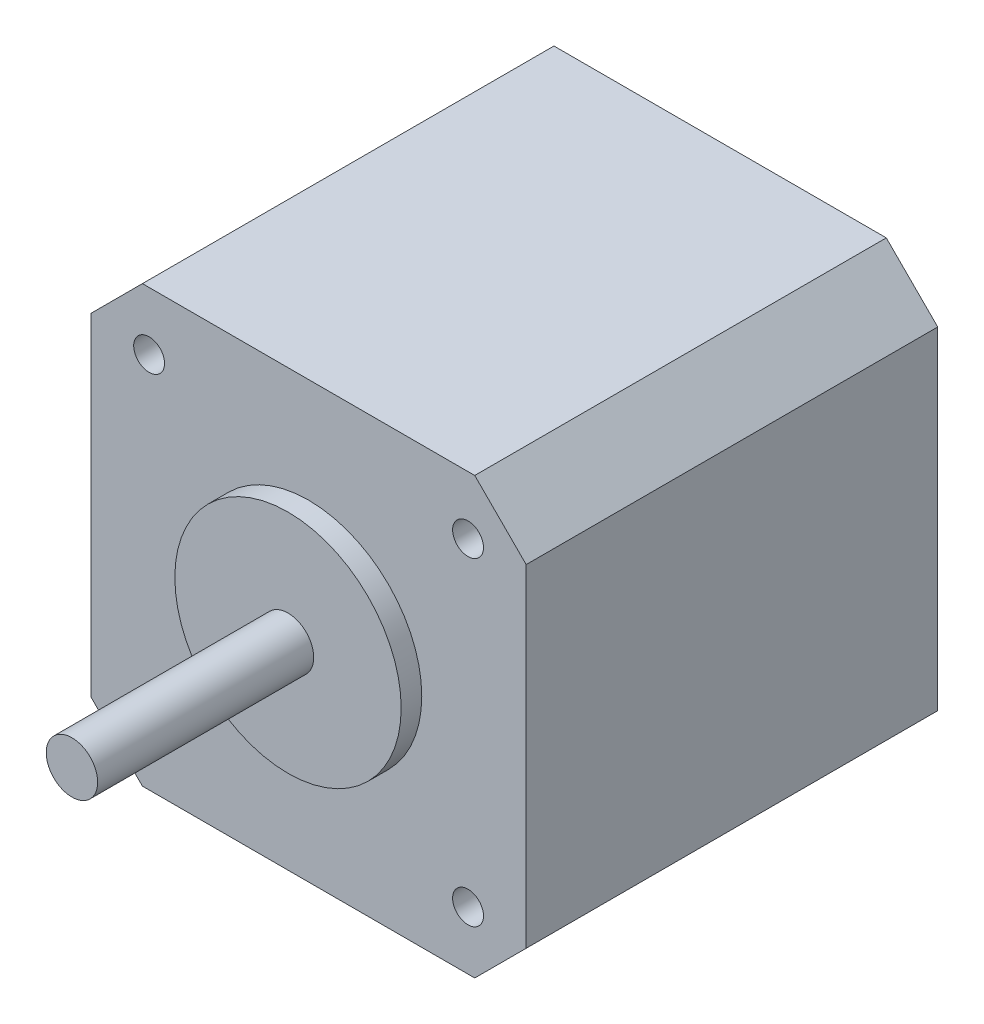
SolidWorks part; units mm, degrees
ref_plane "Alzado" through (0, 0, 0) normal (0, 0, 1) x (1, 0, 0)
ref_plane "Planta" through (0, 0, 0) normal (0, 1, 0) x (1, 0, 0)
ref_plane "Vista lateral" through (0, 0, 0) normal (1, 0, 0) x (0, 0, -1)
sketch "Croquis1" plane through (0, 0, 0) normal (0, 0, 1) x (1, 0, 0)
  line L0 (0, 21.15) -> (0, -21.15) construction
  line L1 (21.15, 21.15) -> (-21.15, 21.15)
  line L2 (21.15, 21.15) -> (21.15, -21.15)
  line L3 (21.15, -21.15) -> (-21.15, -21.15)
  line L4 (-21.15, 21.15) -> (-21.15, -21.15)
  line L5 (21.15, 21.15) -> (-21.15, -21.15) construction
  line L6 (21.15, -21.15) -> (-21.15, 21.15) construction
  line L7 (-21.15, 0) -> (21.15, 0) construction
  circle A0 centre (-15.5, 15.5) radius 1.5
  circle A1 centre (-15.5, -15.5) radius 1.5
  circle A2 centre (15.5, -15.5) radius 1.5
  circle A3 centre (15.5, 15.5) radius 1.5
  point P0 (0, 0)
  point P14 (0, 0)
  point P15 (0, 0)
  point P16 (0, 0)
  dimension "D3" = 3
  dimension "D1" = 42.3
  dimension "D2" = 42.3
  dimension "D4" = 15.5
  dimension "D5" = 15.5
extrude "Saliente-Extruir1" add sketch "Croquis1" along normal mid plane 40
sketch "Croquis2" plane through (0, 0, 20) normal (0, 0, 1) x (1, 0, 0)
  circle A0 centre (0, 0) radius 11
  dimension "D1" = 22
extrude "Saliente-Extruir2" add sketch "Croquis2" along normal blind 2
sketch "Croquis3" plane through (0, 0, 20) normal (0, 0, 1) x (1, 0, 0)
  circle A0 centre (0, 0) radius 2.5
  dimension "D1" = 5
extrude "Saliente-Extruir3" add sketch "Croquis3" along normal blind 23
chamfer "Chaflán1" distance 5 angle 45 4 edges at (-21.15, -21.15, 0) (21.15, -21.15, 0) (-21.15, 21.15, 0) (21.15, 21.15, 0)
